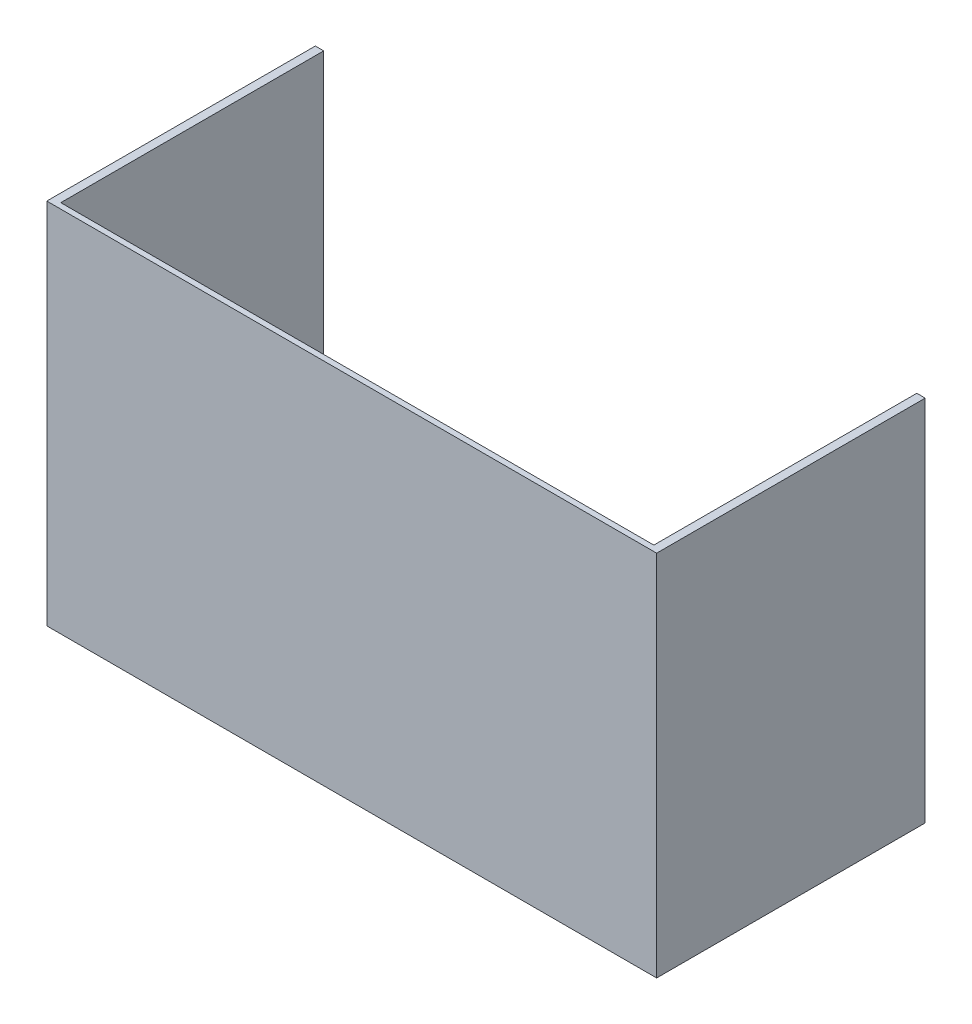
SolidWorks part; units mm, degrees
material "ABS PC"
ref_plane "Front Plane" through (0, 0, 0) normal (0, 0, 1) x (1, 0, 0)
ref_plane "Top Plane" through (0, 0, 0) normal (0, 1, 0) x (1, 0, 0)
ref_plane "Right Plane" through (0, 0, 0) normal (1, 0, 0) x (0, 0, -1)
sketch "Sketch1" plane through (0, 0, 0) normal (0, 0, 1) x (1, 0, 0)
  line L1 (-346.075, 208.788) -> (346.075, 208.788)
  line L2 (-346.075, 208.788) -> (-346.075, -208.788)
  line L3 (-346.075, -208.788) -> (346.075, -208.788)
  line L4 (346.075, 208.788) -> (346.075, -208.788)
  line L5 (-346.075, 208.788) -> (346.075, -208.788) construction
  line L6 (-346.075, -208.788) -> (346.075, 208.788) construction
  point P0 (0, 0)
  dimension "D1" = 417.576
  dimension "D2" = 692.15
extrude "Boss-Extrude1" add sketch "Sketch1" along normal blind 304.8
sketch "Sketch2" plane through (0, 0, 0) normal (0, 0, -1) x (-1, 0, 0)
  line L0 (346.075, -208.788) -> (-346.075, -208.788) construction
  line L1 (-336.55, 208.788) -> (336.55, 208.788)
  line L2 (-336.55, 208.788) -> (-336.55, -208.788)
  line L3 (-336.55, -208.788) -> (336.55, -208.788)
  line L4 (336.55, 208.788) -> (336.55, -208.788)
  line L5 (-336.55, 208.788) -> (336.55, -208.788) construction
  line L6 (-336.55, -208.788) -> (336.55, 208.788) construction
  point P0 (0, 0)
  dimension "D1" = 673.1
extrude "Cut-Extrude1" cut sketch "Sketch2" against normal blind 298.45
